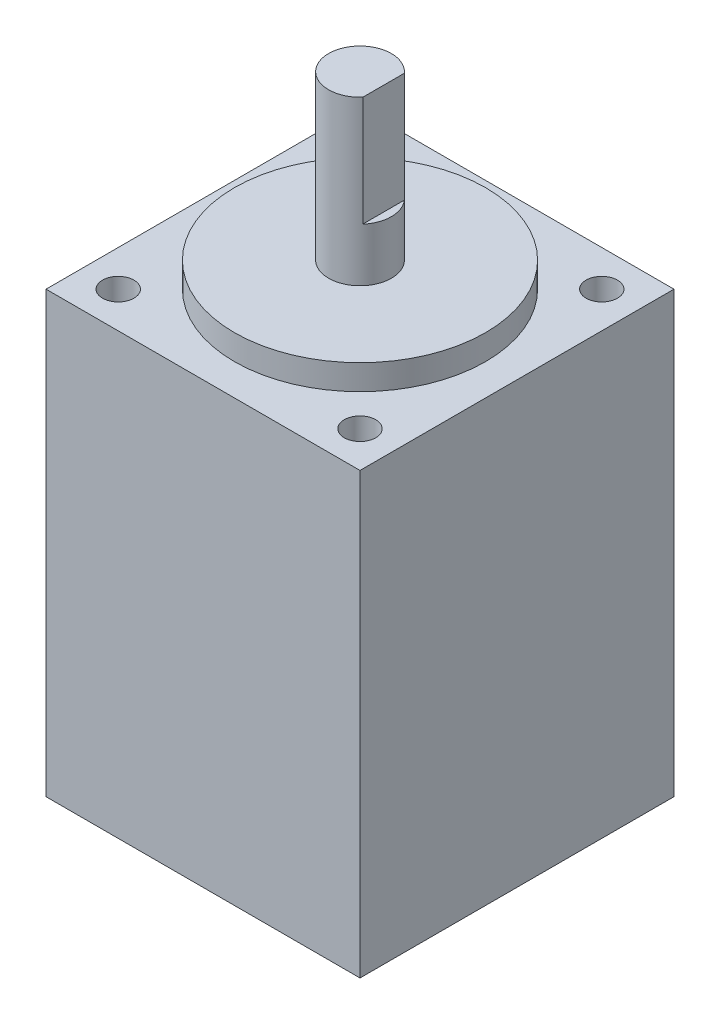
SolidWorks part; units mm, degrees
ref_plane "前视基准面" through (0, 0, 0) normal (0, 0, 1) x (1, 0, 0)
ref_plane "上视基准面" through (0, 0, 0) normal (0, 1, 0) x (1, 0, 0)
ref_plane "右视基准面" through (0, 0, 0) normal (1, 0, 0) x (0, 0, -1)
sketch "草图1" plane through (0, 0, 0) normal (0, 1, 0) x (1, 0, 0)
  line L0 (0, 0) -> (20, 0)
  line L1 (20, 0) -> (20, 20)
  line L2 (0, 0) -> (0, 20)
  line L3 (0, 20) -> (20, 20)
  circle A0 centre (17.7, 2.3) radius 1
  circle A1 centre (17.7, 17.7) radius 1
  circle A2 centre (2.3, 17.7) radius 1
  circle A3 centre (2.3, 2.3) radius 1
extrude "凸台-拉伸1" add sketch "草图1" along normal blind 28
sketch "草图2" plane through (0, 28, 0) normal (0, 1, 0) x (1, 0, 0)
  line L0 (20, 10) -> (0, 10)
  line L1 (20, 0) -> (20, 20) construction
  line L2 (0, 20) -> (0, 0) construction
  circle A0 centre (10, 10) radius 8
extrude "凸台-拉伸2" add sketch "草图2" along normal blind 1.6 contours L0 A0 | L0 A0
sketch "草图3" plane through (0, 29.6, 0) normal (0, 1, 0) x (1, 0, 0)
  circle A0 centre (10, 10) radius 2
extrude "凸台-拉伸3" add sketch "草图3" along normal blind 10.4
sketch "草图4" plane through (0, 40, 0) normal (0, 1, 0) x (1, 0, 0)
  line L0 (8, 10) -> (11.5011, 10)
  line L1 (11.5011, 10) -> (11.5011, 8.6784)
  line L2 (11.5011, 8.6784) -> (11.5011, 11.3216)
  circle A0 centre (10, 10) radius 2 construction
  circle A1 centre (10, 10) radius 2 construction
  circle A2 centre (10, 10) radius 2
  circle M3 centre (10, 10) radius 2
extrude "切除-拉伸4" cut sketch "草图4" against normal blind 7 contours L2 L1 M3
